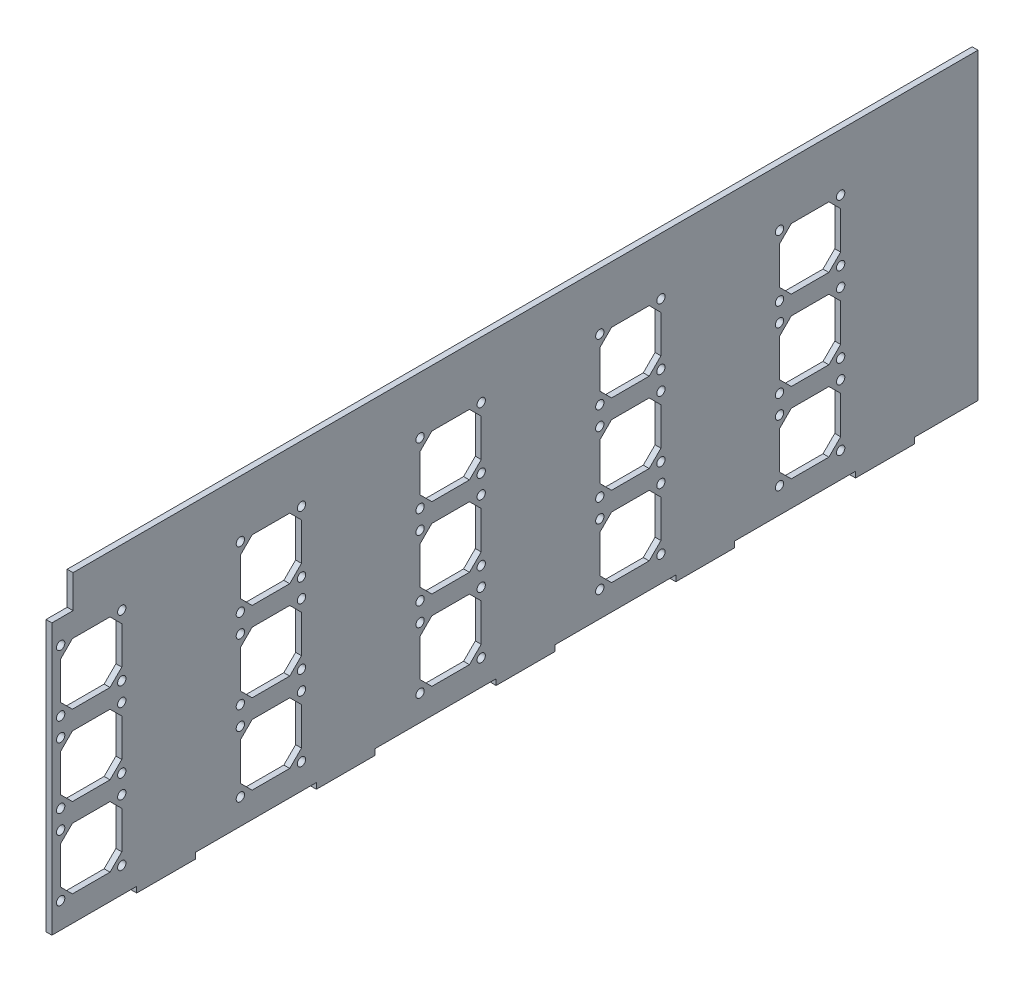
SolidWorks part; units mm, degrees
material "6061-T6 (SS)"
ref_plane "X-Y Datum" through (0, 0, 0) normal (0, 0, 1) x (1, 0, 0)
ref_plane "X-Z Datum" through (0, 0, 0) normal (0, 1, 0) x (1, 0, 0)
ref_plane "Y-Z Datum" through (0, 0, 0) normal (1, 0, 0) x (0, 0, -1)
sketch "Sketch1" plane through (0, 0, 0) normal (1, 0, 0) x (0, 0, -1)
  line L1 (-244.2845, 73.025) -> (244.2845, 73.025)
  line L3 (-244.2845, -73.025) -> (-209.931, -73.025)
  line L4 (244.2845, 73.025) -> (244.2845, 47.625)
  line L5 (-244.2845, 73.025) -> (244.2845, -73.025) construction
  line L6 (-244.2845, -73.025) -> (244.2845, 73.025) construction
  line L13 (244.2845, -60.325) -> (244.2845, -73.025)
  line L14 (-194.056, -73.025) -> (-194.056, 73.025) construction
  line L15 (-209.931, -73.025) -> (-209.931, -76.2)
  line L16 (-209.931, -76.2) -> (-178.181, -76.2)
  line L17 (-178.181, -76.2) -> (-178.181, -73.025)
  line L19 (-178.181, -73.025) -> (-112.903, -73.025)
  line L20 (-112.903, -73.025) -> (-112.903, -76.2)
  line L21 (-112.903, -76.2) -> (-81.153, -76.2)
  line L22 (-81.153, -76.2) -> (-81.153, -73.025)
  line L23 (-15.875, -73.025) -> (-15.875, -76.2)
  line L24 (-15.875, -76.2) -> (15.875, -76.2)
  line L25 (15.875, -76.2) -> (15.875, -73.025)
  line L26 (81.153, -73.025) -> (81.153, -76.2)
  line L27 (81.153, -76.2) -> (112.903, -76.2)
  line L28 (112.903, -76.2) -> (112.903, -73.025)
  line L29 (178.181, -73.025) -> (178.181, -76.2)
  line L30 (178.181, -76.2) -> (209.931, -76.2)
  line L31 (209.931, -76.2) -> (209.931, -73.025)
  line L32 (-81.153, -73.025) -> (-15.875, -73.025)
  line L33 (15.875, -73.025) -> (81.153, -73.025)
  line L34 (112.903, -73.025) -> (178.181, -73.025)
  line L35 (209.931, -73.025) -> (244.2845, -73.025)
  line L37 (244.2845, 47.625) -> (244.2845, -60.325)
  line L38 (-244.2845, 73.025) -> (-255.7145, 73.025)
  line L39 (-255.7145, 73.025) -> (-255.7145, -73.025)
  line L40 (-255.7145, -73.025) -> (-244.2845, -73.025)
  point P0 (0, 0)
  point P14 (-218.8845, 47.625)
  point P27 (-209.931, -73.025)
  point P28 (-178.181, -73.025)
  dimension "D6" = 11.43
  dimension "D1" = 146.05
  dimension "D2" = 488.569
  dimension "D7" = 50.2285
  dimension "D8" = 15.875
  dimension "D9" = 15.875
  dimension "D10" = 3.175
  dimension "D11" = 5
extrude "Boss-Extrude2" add sketch "Sketch1" along normal blind 3.175
sketch "Sketch3" plane through (3.175, 0, 0) normal (1, 0, 0) x (0, 0, -1)
  line L0 (244.2845, -73.025) -> (244.2845, 73.025) construction
  line L1 (-244.2845, 73.025) -> (244.2845, 73.025)
  line L2 (-244.2845, 73.025) -> (-244.2845, 90.805)
  line L3 (-244.2845, 90.805) -> (244.2845, 90.805)
  line L4 (244.2845, 73.025) -> (244.2845, 90.805)
  dimension "D1" = 17.78
extrude "Boss-Extrude3" add sketch "Sketch3" against normal blind 3.175
sketch "Sketch2" plane through (3.175, 0, 0) normal (1, 0, 0) x (0, 0, -1)
  line L0 (-244.2845, 69.215) -> (-241.1095, 69.215)
  line L4 (-244.2845, 69.215) -> (-244.2845, -67.945)
  line L5 (0, 55) -> (0, -55) construction
  line L6 (231.775, -67.945) -> (244.2845, -67.945)
  line L7 (244.2845, 69.215) -> (231.775, 69.215)
  line L9 (244.2845, 69.215) -> (244.2845, -67.945)
  line L14 (238.5695, -33.655) -> (238.5695, -65.405)
  line L15 (241.1095, -67.945) -> (231.775, -67.945)
  line L17 (241.1095, 69.215) -> (231.775, 69.215)
  line L18 (-145.542, -73.025) -> (-145.542, 73.025) construction
  line L19 (-178.181, -73.025) -> (-112.903, -73.025) construction
  line L20 (-244.2845, 73.025) -> (-255.7145, 73.025) construction
  line L37 (-255.7145, -73.025) -> (-209.931, -73.025) construction
  line L38 (238.5695, -33.655) -> (238.5695, 66.675)
  line L39 (-238.5695, 66.675) -> (-238.5695, -33.655)
  line L40 (48.514, -73.025) -> (48.514, 90.805) construction
  line L41 (15.875, -73.025) -> (81.153, -73.025) construction
  line L42 (244.2845, 90.805) -> (-244.2845, 90.805) construction
  line L87 (-238.5695, -33.655) -> (-238.5695, -65.405)
  line L88 (-241.1095, -67.945) -> (-244.2845, -67.945)
  line L90 (-135.8265, 69.215) -> (-135.8265, -67.945)
  line L93 (-135.8265, 69.215) -> (-132.6515, 69.215)
  line L95 (-46.1645, 69.215) -> (-42.9895, 69.215)
  line L96 (-46.1645, 69.215) -> (-46.1645, -67.945)
  line L97 (-135.8265, -67.945) -> (-132.6515, -67.945)
  line L98 (-132.6515, -67.945) -> (-132.6515, 69.215)
  line L99 (-42.9895, -67.945) -> (-42.9895, 69.215)
  line L100 (-46.1645, -67.945) -> (-42.9895, -67.945)
  line L101 (43.4975, 69.215) -> (46.6725, 69.215)
  line L102 (43.4975, 69.215) -> (43.4975, -67.945)
  line L103 (46.6725, -67.945) -> (46.6725, 69.215)
  line L104 (43.4975, -67.945) -> (46.6725, -67.945)
  line L105 (133.1595, 69.215) -> (136.3345, 69.215)
  line L106 (133.1595, 69.215) -> (133.1595, -67.945)
  line L107 (136.3345, -67.945) -> (136.3345, 69.215)
  line L108 (133.1595, -67.945) -> (136.3345, -67.945)
  arc A16 (238.5695, -65.405) -> (241.1095, -67.945) centre (241.1095, -65.405) ccw
  arc A20 (241.1095, 69.215) -> (238.5695, 66.675) centre (241.1095, 66.675) ccw
  arc A21 (-241.1095, 69.215) -> (-238.5695, 66.675) centre (-241.1095, 66.675) cw
  arc A22 (-238.5695, -65.405) -> (-241.1095, -67.945) centre (-241.1095, -65.405) cw
  point P8 (-145.542, 0)
  point P12 (-241.1095, 69.215)
  point P38 (-143.764, -67.945)
  point P41 (-124.714, 69.215)
  point P44 (-143.764, 69.215)
  point P86 (238.5695, 69.215)
  point P90 (-238.5695, 69.215)
  point P91 (-241.1095, 69.215)
  dimension "D4" = 19.05
  dimension "D7" = 3.175
  dimension "D9" = 2.54
  dimension "D10" = 2.54
  dimension "D11" = 2.54
  dimension "D1" = 142.24
  dimension "D2" = 137.16
  dimension "D3" = 3.175
  dimension "D5" = 142.24
  dimension "D6" = 4
  dimension "D8" = 137.16
extrude "Cut-Extrude1" [suppressed] cut sketch "Sketch2" against normal through all both
sketch "Sketch4" plane through (3.175, 0, 0) normal (1, 0, 0) x (0, 0, -1)
  line L0 (-134.239, -67.945) -> (-134.239, 69.215) construction
  line L5 (-171.958, 36.322) -> (-96.52, 36.322)
  line L6 (-171.958, 36.322) -> (-171.958, -35.052)
  line L7 (-171.958, -35.052) -> (-96.52, -35.052)
  line L8 (-96.52, 36.322) -> (-96.52, -35.052)
  line L9 (-171.958, 36.322) -> (-96.52, -35.052) construction
  line L10 (-171.958, -35.052) -> (-96.52, 36.322) construction
  line L11 (-97.282, 36.322) -> (-21.844, 36.322)
  line L12 (-97.282, 36.322) -> (-97.282, -35.052)
  line L13 (-97.282, -35.052) -> (-21.844, -35.052)
  line L14 (-21.844, 36.322) -> (-21.844, -35.052)
  line L15 (-22.606, 36.322) -> (52.832, 36.322)
  line L16 (-22.606, 36.322) -> (-22.606, -35.052)
  line L17 (-22.606, -35.052) -> (52.832, -35.052)
  line L18 (52.832, 36.322) -> (52.832, -35.052)
  line L19 (52.07, 36.322) -> (127.508, 36.322)
  line L20 (52.07, 36.322) -> (52.07, -35.052)
  line L21 (52.07, -35.052) -> (127.508, -35.052)
  line L22 (127.508, 36.322) -> (127.508, -35.052)
  line L23 (-209.931, -73.025) -> (-209.931, -76.2) construction
  point P0 (0, 0)
  point P8 (-134.239, 0.635)
  dimension "D1" = 75.438
  dimension "D2" = 71.374
  dimension "D4" = 112.649
  dimension "D3" = 4
extrude "Cut-Extrude3" [suppressed] cut sketch "Sketch4" against normal through all both
sketch "Sketch5" plane through (3.175, 0, 0) normal (1, 0, 0) x (0, 0, -1)
  line L0 (-145.542, -73.025) -> (-145.542, 90.805) construction
  line L1 (-178.181, -73.025) -> (-112.903, -73.025) construction
  line L2 (244.2845, 90.805) -> (-244.2845, 90.805) construction
  line L3 (-145.542, 69.215) -> (-148.082, 69.215)
  line L4 (-148.082, 69.215) -> (-148.082, -67.945)
  line L5 (-148.082, -67.945) -> (-145.542, -67.945)
  line L6 (-145.542, -67.945) -> (-126.492, -67.945)
  line L7 (-126.492, -67.945) -> (-126.492, 69.215)
  line L8 (-126.492, 69.215) -> (-145.542, 69.215)
  line L9 (-48.514, 69.215) -> (-51.054, 69.215)
  line L10 (-29.464, -67.945) -> (-29.464, 69.215)
  line L11 (-29.464, 69.215) -> (-48.514, 69.215)
  line L12 (-51.054, 69.215) -> (-51.054, -67.945)
  line L13 (-48.514, -67.945) -> (-29.464, -67.945)
  line L14 (-51.054, -67.945) -> (-48.514, -67.945)
  line L15 (48.514, 69.215) -> (45.974, 69.215)
  line L16 (67.564, -67.945) -> (67.564, 69.215)
  line L17 (67.564, 69.215) -> (48.514, 69.215)
  line L18 (45.974, 69.215) -> (45.974, -67.945)
  line L19 (48.514, -67.945) -> (67.564, -67.945)
  line L20 (45.974, -67.945) -> (48.514, -67.945)
  line L21 (145.542, 69.215) -> (143.002, 69.215)
  line L22 (164.592, -67.945) -> (164.592, 69.215)
  line L23 (164.592, 69.215) -> (145.542, 69.215)
  line L24 (143.002, 69.215) -> (143.002, -67.945)
  line L25 (145.542, -67.945) -> (164.592, -67.945)
  line L26 (143.002, -67.945) -> (145.542, -67.945)
  line L27 (242.57, 69.215) -> (240.03, 69.215)
  line L29 (261.62, 69.215) -> (242.57, 69.215)
  line L30 (240.03, 69.215) -> (240.03, -67.945)
  line L31 (242.57, -67.945) -> (261.62, -67.945)
  line L32 (240.03, -67.945) -> (242.57, -67.945)
  line L33 (-242.57, 69.215) -> (-245.11, 69.215)
  line L34 (-223.52, 69.215) -> (-242.57, 69.215)
  line L36 (-223.52, -67.945) -> (-223.52, 69.215)
  line L37 (-242.57, -67.945) -> (-223.52, -67.945)
  line L38 (-245.11, -67.945) -> (-242.57, -67.945)
  line L39 (-245.11, 69.215) -> (-245.11, -67.945) [skipped]
  line L40 (261.62, -67.945) -> (261.62, 69.215) [skipped]
  line L41 (261.62, 69.215) -> (262.3511, 69.215)
  line L42 (262.3511, 69.215) -> (262.3511, -67.945)
  line L43 (262.3511, -67.945) -> (261.62, -67.945)
  line L44 (-245.11, 69.215) -> (-245.4466, 69.215)
  line L45 (-245.4466, 69.215) -> (-245.4466, -67.945)
  line L46 (-245.4466, -67.945) -> (-245.11, -67.945)
  dimension "D1" = 2.54
  dimension "D2" = 19.05
  dimension "D3" = 137.16
  dimension "D4" = 142.24
  dimension "D5" = 5
  dimension "D6" = 2
extrude "Cut-Extrude4" [suppressed] cut sketch "Sketch5" against normal through all both
fillet "Fillet1" [suppressed] radius 2.54
sketch "Sketch6" plane through (3.175, 0, 0) normal (1, 0, 0) x (0, 0, -1)
  line L0 (-234.4833, -67.945) -> (-234.4833, 69.215) construction
  line L3 (-252.8544, 60.1404) -> (-219.0037, 60.1404) construction
  circle A0 centre (-250.9833, 60.1404) radius 2.25
  circle A1 centre (-217.9833, 60.1404) radius 2.25
  circle A2 centre (-250.9833, 27.1204) radius 2.25
  circle A3 centre (-217.9833, 27.1204) radius 2.25
  circle A4 centre (-250.9833, 16.9604) radius 2.25
  circle A5 centre (-250.9833, -16.0596) radius 2.25
  circle A6 centre (-217.9833, -16.0596) radius 2.25
  circle A7 centre (-217.9833, 16.9604) radius 2.25
  circle A8 centre (-250.9833, -26.2196) radius 2.25
  circle A9 centre (-250.9833, -59.2396) radius 2.25
  circle A10 centre (-217.9833, -59.2396) radius 2.25
  circle A11 centre (-217.9833, -26.2196) radius 2.25
  circle A12 centre (-153.9553, 60.1404) radius 2.25
  circle A13 centre (-120.9553, 60.1404) radius 2.25
  circle A14 centre (-153.9553, 27.1204) radius 2.25
  circle A15 centre (-120.9553, 16.9604) radius 2.25
  circle A16 centre (-153.9553, 16.9604) radius 2.25
  circle A17 centre (-153.9553, -16.0596) radius 2.25
  circle A18 centre (-120.9553, 27.1204) radius 2.25
  circle A19 centre (-120.9553, -16.0596) radius 2.25
  circle A20 centre (-120.9553, -26.2196) radius 2.25
  circle A21 centre (-153.9553, -26.2196) radius 2.25
  circle A22 centre (-153.9553, -59.2396) radius 2.25
  circle A23 centre (-120.9553, -59.2396) radius 2.25
  circle A24 centre (-56.9273, 60.1404) radius 2.25
  circle A25 centre (-23.9273, 60.1404) radius 2.25
  circle A26 centre (-56.9273, 27.1204) radius 2.25
  circle A27 centre (-23.9273, 16.9604) radius 2.25
  circle A28 centre (-56.9273, 16.9604) radius 2.25
  circle A29 centre (-56.9273, -16.0596) radius 2.25
  circle A30 centre (-23.9273, 27.1204) radius 2.25
  circle A31 centre (-23.9273, -16.0596) radius 2.25
  circle A32 centre (-23.9273, -26.2196) radius 2.25
  circle A33 centre (-56.9273, -26.2196) radius 2.25
  circle A34 centre (-56.9273, -59.2396) radius 2.25
  circle A35 centre (-23.9273, -59.2396) radius 2.25
  circle A36 centre (40.1007, 60.1404) radius 2.25
  circle A37 centre (73.1007, 60.1404) radius 2.25
  circle A38 centre (40.1007, 27.1204) radius 2.25
  circle A39 centre (73.1007, 16.9604) radius 2.25
  circle A40 centre (40.1007, 16.9604) radius 2.25
  circle A41 centre (40.1007, -16.0596) radius 2.25
  circle A42 centre (73.1007, 27.1204) radius 2.25
  circle A43 centre (73.1007, -16.0596) radius 2.25
  circle A44 centre (73.1007, -26.2196) radius 2.25
  circle A45 centre (40.1007, -26.2196) radius 2.25
  circle A46 centre (40.1007, -59.2396) radius 2.25
  circle A47 centre (73.1007, -59.2396) radius 2.25
  circle A48 centre (137.1287, 60.1404) radius 2.25
  circle A49 centre (170.1287, 60.1404) radius 2.25
  circle A50 centre (137.1287, 27.1204) radius 2.25
  circle A51 centre (170.1287, 16.9604) radius 2.25
  circle A52 centre (137.1287, 16.9604) radius 2.25
  circle A53 centre (137.1287, -16.0596) radius 2.25
  circle A54 centre (170.1287, 27.1204) radius 2.25
  circle A55 centre (170.1287, -16.0596) radius 2.25
  circle A56 centre (170.1287, -26.2196) radius 2.25
  circle A57 centre (137.1287, -26.2196) radius 2.25
  circle A58 centre (137.1287, -59.2396) radius 2.25
  circle A59 centre (170.1287, -59.2396) radius 2.25
  dimension "D1" = 16.5
  dimension "D2" = 2
  dimension "D3" = 3
  dimension "D4" = 5
extrude "Cut-Extrude5" cut sketch "Sketch6" against normal through all both and the other way through all
sketch "Sketch7" [suppressed] plane through (3.175, 0, 0) normal (1, 0, 0) x (0, 0, -1)
  line L0 (-234.4833, -67.945) -> (-234.4833, 69.215) construction
  line L3 (-250.9833, 60.1404) -> (-250.9833, 27.1204) construction
  line L4 (-250.9833, 43.6304) -> (-223.52, 43.6304) construction
  line L5 (-223.52, -67.945) -> (-223.52, 69.215) construction
  line L7 (-250.9833, 60.1304) -> (-217.9833, 60.1304)
  line L8 (-250.9833, 60.1304) -> (-250.9833, 27.1304)
  line L9 (-250.9833, 27.1304) -> (-217.9833, 27.1304)
  line L10 (-217.9833, 60.1304) -> (-217.9833, 27.1304)
  line L11 (-250.9833, 60.1304) -> (-217.9833, 27.1304) construction
  line L12 (-250.9833, 27.1304) -> (-217.9833, 60.1304) construction
  arc A0 (-250.9833, 52.5204) -> (-243.3633, 60.1304) centre (-242.8867, 52.0333) cw
  point P14 (-237.2516, 43.6304)
  point P15 (-234.4833, 43.6304)
  dimension "D1" = 0
  dimension "D2" = 33
  dimension "D3" = 33
  dimension "D4" = 7.62
  dimension "D5" = 7.62
sketch "Sketch8" plane through (3.175, 0, 0) normal (1, 0, 0) x (0, 0, -1)
  line L0 (-250.9833, 60.1404) -> (-217.9833, 60.1404) construction
  line L1 (-234.4833, 60.1404) -> (-234.4833, -73.025) construction
  line L2 (-255.7145, -73.025) -> (-209.931, -73.025) construction
  line L3 (-250.9833, 60.1404) -> (-250.9833, 27.1204) construction
  line L4 (-250.9833, 43.6304) -> (-217.9833, 43.6304) construction
  line L5 (-250.9833, 53.7904) -> (-244.6333, 60.1304)
  line L6 (-244.6333, 60.1304) -> (-224.3333, 60.1304)
  line L7 (-250.9833, 53.7904) -> (-250.9833, 33.4704)
  line L8 (-244.6333, 27.1304) -> (-224.3333, 27.1304)
  line L9 (-217.9833, 53.7904) -> (-217.9833, 33.4704)
  line L10 (-250.9833, 60.1304) -> (-217.9833, 27.1304) construction
  line L11 (-250.9833, 27.1304) -> (-217.9833, 60.1304) construction
  line L12 (-217.9833, 53.7904) -> (-224.3333, 60.1304)
  line L13 (-217.9833, 33.4704) -> (-224.3333, 27.1304)
  line L14 (-250.9833, 33.4704) -> (-244.6333, 27.1304)
  line L15 (-250.9833, 10.6104) -> (-244.6333, 16.9504)
  line L16 (-244.6333, 16.9504) -> (-224.3333, 16.9504)
  line L17 (-217.9833, 10.6104) -> (-224.3333, 16.9504)
  line L18 (-250.9833, 10.6104) -> (-250.9833, -9.7096)
  line L19 (-250.9833, -9.7096) -> (-244.6333, -16.0496)
  line L20 (-244.6333, -16.0496) -> (-224.3333, -16.0496)
  line L21 (-217.9833, 10.6104) -> (-217.9833, -9.7096)
  line L22 (-217.9833, -9.7096) -> (-224.3333, -16.0496)
  line L23 (-250.9833, -32.5696) -> (-244.6333, -26.2296)
  line L24 (-244.6333, -26.2296) -> (-224.3333, -26.2296)
  line L25 (-217.9833, -32.5696) -> (-224.3333, -26.2296)
  line L26 (-250.9833, -32.5696) -> (-250.9833, -52.8896)
  line L27 (-250.9833, -52.8896) -> (-244.6333, -59.2296)
  line L28 (-244.6333, -59.2296) -> (-224.3333, -59.2296)
  line L29 (-217.9833, -32.5696) -> (-217.9833, -52.8896)
  line L30 (-217.9833, -52.8896) -> (-224.3333, -59.2296)
  line L31 (-153.9553, 53.7904) -> (-147.6053, 60.1304)
  line L32 (-147.6053, 60.1304) -> (-127.3053, 60.1304)
  line L33 (-120.9553, 53.7904) -> (-127.3053, 60.1304)
  line L34 (-153.9553, 53.7904) -> (-153.9553, 33.4704)
  line L35 (-153.9553, 33.4704) -> (-147.6053, 27.1304)
  line L36 (-147.6053, 27.1304) -> (-127.3053, 27.1304)
  line L37 (-120.9553, 53.7904) -> (-120.9553, 33.4704)
  line L38 (-120.9553, 33.4704) -> (-127.3053, 27.1304)
  line L39 (-147.6053, 16.9504) -> (-127.3053, 16.9504)
  line L40 (-120.9553, 10.6104) -> (-127.3053, 16.9504)
  line L41 (-120.9553, 10.6104) -> (-120.9553, -9.7096)
  line L42 (-120.9553, -9.7096) -> (-127.3053, -16.0496)
  line L43 (-147.6053, -16.0496) -> (-127.3053, -16.0496)
  line L44 (-153.9553, -9.7096) -> (-147.6053, -16.0496)
  line L45 (-153.9553, 10.6104) -> (-153.9553, -9.7096)
  line L46 (-153.9553, 10.6104) -> (-147.6053, 16.9504)
  line L47 (-120.9553, -52.8896) -> (-127.3053, -59.2296)
  line L48 (-120.9553, -32.5696) -> (-120.9553, -52.8896)
  line L49 (-120.9553, -32.5696) -> (-127.3053, -26.2296)
  line L50 (-147.6053, -26.2296) -> (-127.3053, -26.2296)
  line L51 (-153.9553, -32.5696) -> (-147.6053, -26.2296)
  line L52 (-153.9553, -32.5696) -> (-153.9553, -52.8896)
  line L53 (-153.9553, -52.8896) -> (-147.6053, -59.2296)
  line L54 (-147.6053, -59.2296) -> (-127.3053, -59.2296)
  line L55 (-56.9273, 53.7904) -> (-50.5773, 60.1304)
  line L56 (-50.5773, 60.1304) -> (-30.2773, 60.1304)
  line L57 (-23.9273, 53.7904) -> (-30.2773, 60.1304)
  line L58 (-56.9273, 53.7904) -> (-56.9273, 33.4704)
  line L59 (-56.9273, 33.4704) -> (-50.5773, 27.1304)
  line L60 (-50.5773, 27.1304) -> (-30.2773, 27.1304)
  line L61 (-23.9273, 53.7904) -> (-23.9273, 33.4704)
  line L62 (-23.9273, 33.4704) -> (-30.2773, 27.1304)
  line L63 (-50.5773, 16.9504) -> (-30.2773, 16.9504)
  line L64 (-23.9273, 10.6104) -> (-30.2773, 16.9504)
  line L65 (-23.9273, 10.6104) -> (-23.9273, -9.7096)
  line L66 (-23.9273, -9.7096) -> (-30.2773, -16.0496)
  line L67 (-50.5773, -16.0496) -> (-30.2773, -16.0496)
  line L68 (-56.9273, -9.7096) -> (-50.5773, -16.0496)
  line L69 (-56.9273, 10.6104) -> (-56.9273, -9.7096)
  line L70 (-56.9273, 10.6104) -> (-50.5773, 16.9504)
  line L71 (-23.9273, -52.8896) -> (-30.2773, -59.2296)
  line L72 (-23.9273, -32.5696) -> (-23.9273, -52.8896)
  line L73 (-23.9273, -32.5696) -> (-30.2773, -26.2296)
  line L74 (-50.5773, -26.2296) -> (-30.2773, -26.2296)
  line L75 (-56.9273, -32.5696) -> (-50.5773, -26.2296)
  line L76 (-56.9273, -32.5696) -> (-56.9273, -52.8896)
  line L77 (-56.9273, -52.8896) -> (-50.5773, -59.2296)
  line L78 (-50.5773, -59.2296) -> (-30.2773, -59.2296)
  line L79 (40.1007, 53.7904) -> (46.4507, 60.1304)
  line L80 (46.4507, 60.1304) -> (66.7507, 60.1304)
  line L81 (73.1007, 53.7904) -> (66.7507, 60.1304)
  line L82 (40.1007, 53.7904) -> (40.1007, 33.4704)
  line L83 (40.1007, 33.4704) -> (46.4507, 27.1304)
  line L84 (46.4507, 27.1304) -> (66.7507, 27.1304)
  line L85 (73.1007, 53.7904) -> (73.1007, 33.4704)
  line L86 (73.1007, 33.4704) -> (66.7507, 27.1304)
  line L87 (46.4507, 16.9504) -> (66.7507, 16.9504)
  line L88 (73.1007, 10.6104) -> (66.7507, 16.9504)
  line L89 (73.1007, 10.6104) -> (73.1007, -9.7096)
  line L90 (73.1007, -9.7096) -> (66.7507, -16.0496)
  line L91 (46.4507, -16.0496) -> (66.7507, -16.0496)
  line L92 (40.1007, -9.7096) -> (46.4507, -16.0496)
  line L93 (40.1007, 10.6104) -> (40.1007, -9.7096)
  line L94 (40.1007, 10.6104) -> (46.4507, 16.9504)
  line L95 (73.1007, -52.8896) -> (66.7507, -59.2296)
  line L96 (73.1007, -32.5696) -> (73.1007, -52.8896)
  line L97 (73.1007, -32.5696) -> (66.7507, -26.2296)
  line L98 (46.4507, -26.2296) -> (66.7507, -26.2296)
  line L99 (40.1007, -32.5696) -> (46.4507, -26.2296)
  line L100 (40.1007, -32.5696) -> (40.1007, -52.8896)
  line L101 (40.1007, -52.8896) -> (46.4507, -59.2296)
  line L102 (46.4507, -59.2296) -> (66.7507, -59.2296)
  line L103 (137.1287, 53.7904) -> (143.4787, 60.1304)
  line L104 (143.4787, 60.1304) -> (163.7787, 60.1304)
  line L105 (170.1287, 53.7904) -> (163.7787, 60.1304)
  line L106 (137.1287, 53.7904) -> (137.1287, 33.4704)
  line L107 (137.1287, 33.4704) -> (143.4787, 27.1304)
  line L108 (143.4787, 27.1304) -> (163.7787, 27.1304)
  line L109 (170.1287, 53.7904) -> (170.1287, 33.4704)
  line L110 (170.1287, 33.4704) -> (163.7787, 27.1304)
  line L111 (143.4787, 16.9504) -> (163.7787, 16.9504)
  line L112 (170.1287, 10.6104) -> (163.7787, 16.9504)
  line L113 (170.1287, 10.6104) -> (170.1287, -9.7096)
  line L114 (170.1287, -9.7096) -> (163.7787, -16.0496)
  line L115 (143.4787, -16.0496) -> (163.7787, -16.0496)
  line L116 (137.1287, -9.7096) -> (143.4787, -16.0496)
  line L117 (137.1287, 10.6104) -> (137.1287, -9.7096)
  line L118 (137.1287, 10.6104) -> (143.4787, 16.9504)
  line L119 (170.1287, -52.8896) -> (163.7787, -59.2296)
  line L120 (170.1287, -32.5696) -> (170.1287, -52.8896)
  line L121 (170.1287, -32.5696) -> (163.7787, -26.2296)
  line L122 (143.4787, -26.2296) -> (163.7787, -26.2296)
  line L123 (137.1287, -32.5696) -> (143.4787, -26.2296)
  line L124 (137.1287, -32.5696) -> (137.1287, -52.8896)
  line L125 (137.1287, -52.8896) -> (143.4787, -59.2296)
  line L126 (143.4787, -59.2296) -> (163.7787, -59.2296)
  point P12 (-234.4833, 43.6304)
  dimension "D1" = 33
  dimension "D2" = 33
  dimension "D3" = 6.35
  dimension "D4" = 6.35
  dimension "D5" = 3
  dimension "D6" = 5
extrude "Cut-Extrude7" cut sketch "Sketch8" against normal through all both
